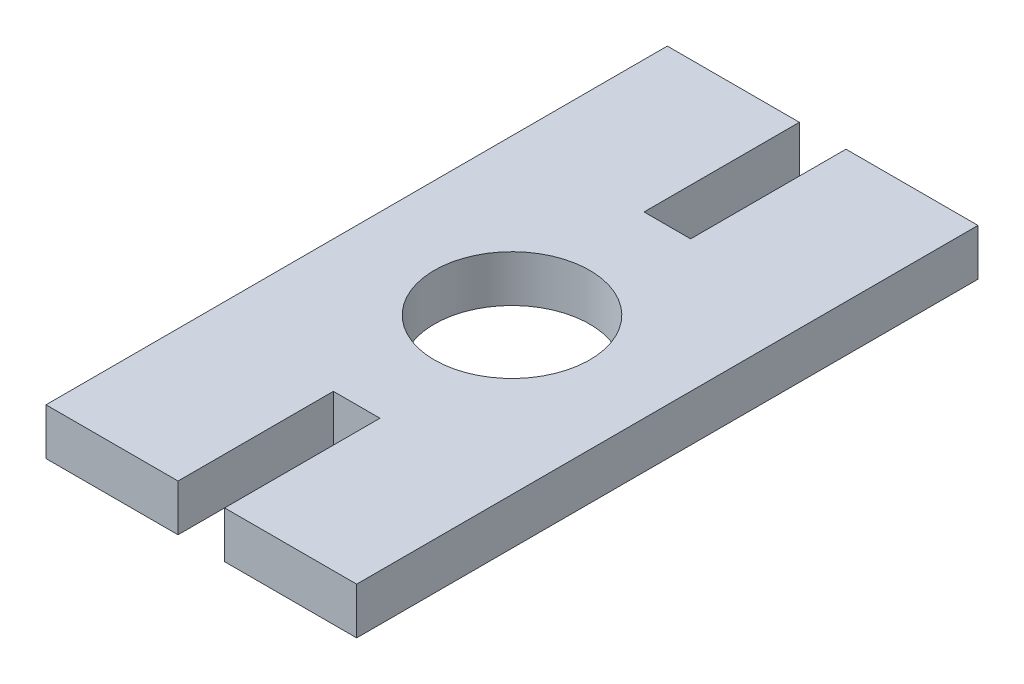
SolidWorks part; units mm, degrees
ref_plane "前视基准面" through (0, 0, 0) normal (0, 0, 1) x (1, 0, 0)
ref_plane "上视基准面" through (0, 0, 0) normal (0, 1, 0) x (1, 0, 0)
ref_plane "右视基准面" through (0, 0, 0) normal (1, 0, 0) x (0, 0, -1)
sketch "草图2" plane through (0, 0, 0) normal (0, 1, 0) x (1, 0, 0)
  line L1 (-1.5, -10) -> (1.5, -10)
  line L2 (1.5, 20) -> (10, 20)
  line L3 (-1.5, 10) -> (1.5, 10)
  line L4 (-10, -20) -> (-1.5, -20)
  line L5 (1.5, 20) -> (2, 20)
  line L6 (-10, -20) -> (-10, 20)
  line L7 (-2, -20) -> (-1.5, -20)
  line L8 (-10, -12) -> (-10, 12)
  line L11 (-10, 20) -> (-1.5, 20)
  line L12 (10, -20) -> (10, 20)
  line L13 (-10, -20) -> (10, 20) construction
  line L14 (-1.5, -20) -> (-1.5, -10)
  line L15 (-10, 20) -> (10, -20) construction
  line L16 (1.5, -20) -> (1.5, -10)
  line L17 (1.5, -20) -> (10, -20)
  line L19 (-1.5, 10) -> (-1.5, 20)
  line L22 (1.5, 10) -> (1.5, 20)
  circle A0 centre (0, 0) radius 5
  point P0 (0, 0)
extrude "凸台-拉伸1" add sketch "草图2" along normal blind 3 contours L22 L3 L19 L11 L6 L4 L14 L1 L16 L17 L12 L2 A0
